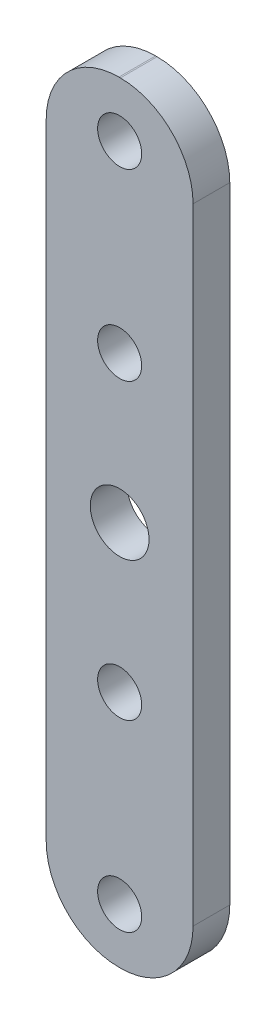
SolidWorks part; units mm, degrees
ref_plane "Front Plane" through (0, 0, 0) normal (0, 0, 1) x (1, 0, 0)
ref_plane "Top Plane" through (0, 0, 0) normal (0, 1, 0) x (1, 0, 0)
ref_plane "Right Plane" through (0, 0, 0) normal (1, 0, 0) x (0, 0, -1)
sketch "Sketch1" plane through (0, 0, 0) normal (0, 0, 1) x (1, 0, 0)
  line L0 (20, 52.5) -> (73.6377, 52.5) construction
  line L1 (9.9, 0) -> (10.1, 0)
  line L2 (0, 9.9) -> (0, 95.1)
  line L3 (9.9, 105) -> (10.1, 105)
  line L4 (20, 9.9) -> (20, 95.1)
  line L5 (10, 0) -> (10, 129.5777) construction
  circle A0 centre (10, 52.5) radius 4
  circle A1 centre (10, 97.5) radius 3
  circle A2 centre (10, 7.5) radius 3
  circle A3 centre (10, 32.5) radius 3
  circle A4 centre (10, 72.5) radius 3
  arc A5 (10.1, 105) -> (20, 95.1) centre (10.1, 95.1) cw
  arc A6 (0, 95.1) -> (9.9, 105) centre (9.9, 95.1) cw
  arc A7 (10.1, 0) -> (20, 9.9) centre (10.1, 9.9) ccw
  arc A8 (9.9, 0) -> (0, 9.9) centre (9.9, 9.9) cw
  point P21 (20, 105)
  point P24 (0, 105)
  point P27 (20, 0)
  point P30 (0, 0)
  dimension "D3" = 8
  dimension "D4" = 6
  dimension "D9" = 9.9
  dimension "D1" = 105
  dimension "D2" = 20
  dimension "D5" = 40
  dimension "D6" = 40
  dimension "D7" = 90
  dimension "D8" = 90
extrude "Boss-Extrude1" add sketch "Sketch1" along normal blind 5
